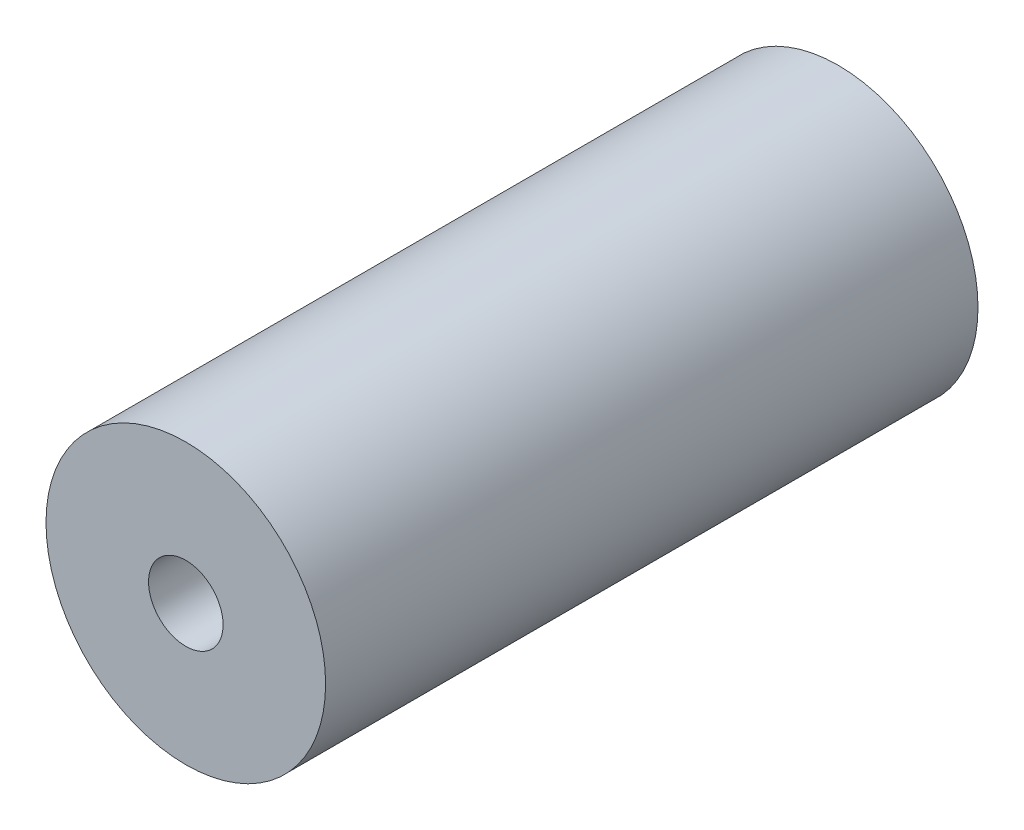
SolidWorks part; units mm, degrees
ref_plane "Front Plane" through (0, 0, 0) normal (0, 0, 1) x (1, 0, 0)
ref_plane "Top Plane" through (0, 0, 0) normal (0, 1, 0) x (1, 0, 0)
ref_plane "Right Plane" through (0, 0, 0) normal (1, 0, 0) x (0, 0, -1)
sketch "Sketch1" plane through (0, 0, 0) normal (0, 0, 1) x (1, 0, 0)
  circle A0 centre (0, 0) radius 3
  circle A1 centre (0, 0) radius 0.8
extrude "Boss-Extrude1" add sketch "Sketch1" along normal blind 14
